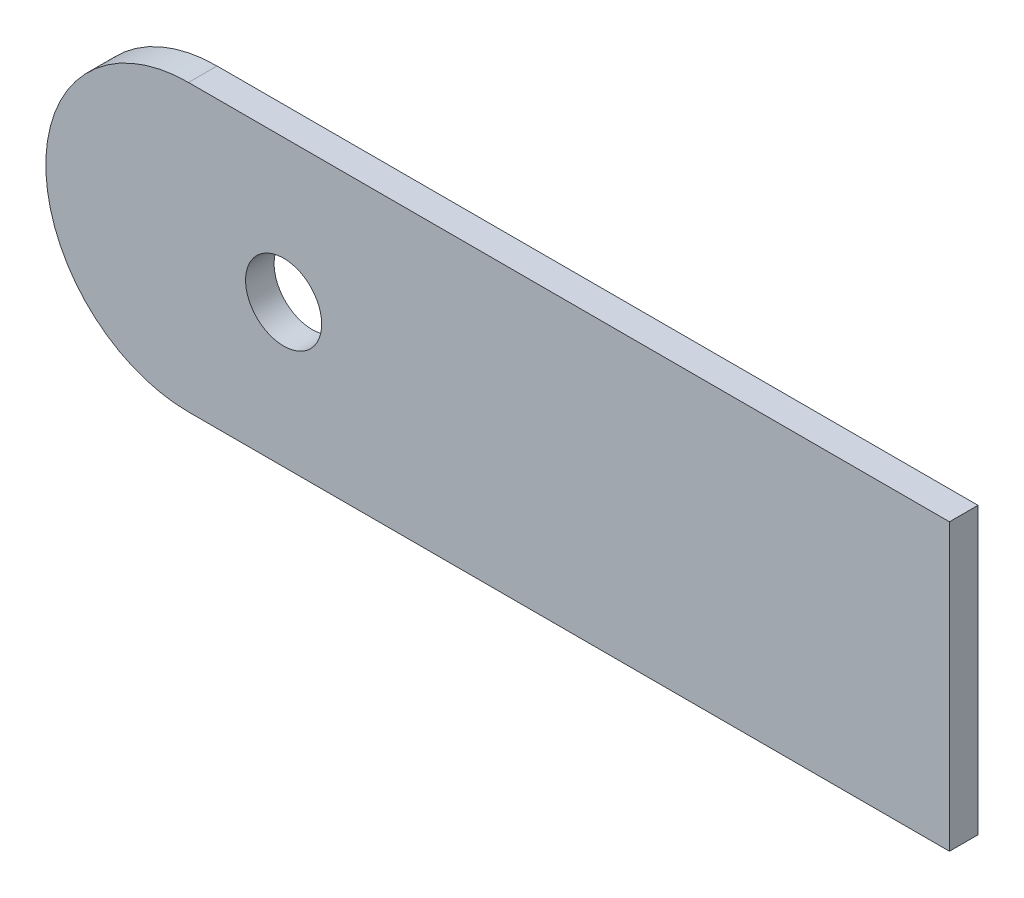
SolidWorks part; units mm, degrees
ref_plane "Front Plane" through (0, 0, 0) normal (0, 0, 1) x (1, 0, 0)
ref_plane "Top Plane" through (0, 0, 0) normal (0, 1, 0) x (1, 0, 0)
ref_plane "Right Plane" through (0, 0, 0) normal (1, 0, 0) x (0, 0, -1)
sketch "Sketch1" plane through (0, 0, 0) normal (0, 0, 1) x (1, 0, 0)
  line L1 (-40, 15) -> (40, 15)
  line L3 (-40, -15) -> (40, -15)
  line L4 (40, 15) -> (40, -15)
  line L5 (-40, 15) -> (40, -15) construction
  line L6 (-40, -15) -> (40, 15) construction
  arc A0 (-40, 15) -> (-40, -15) centre (-40, 0) ccw
  circle A2 centre (-30, 0) radius 4
  point P0 (0, 0)
  dimension "D3" = 10
  dimension "D4" = 8
  dimension "D1" = 30
  dimension "D2" = 80
extrude "Boss-Extrude1" add sketch "Sketch1" along normal blind 3
